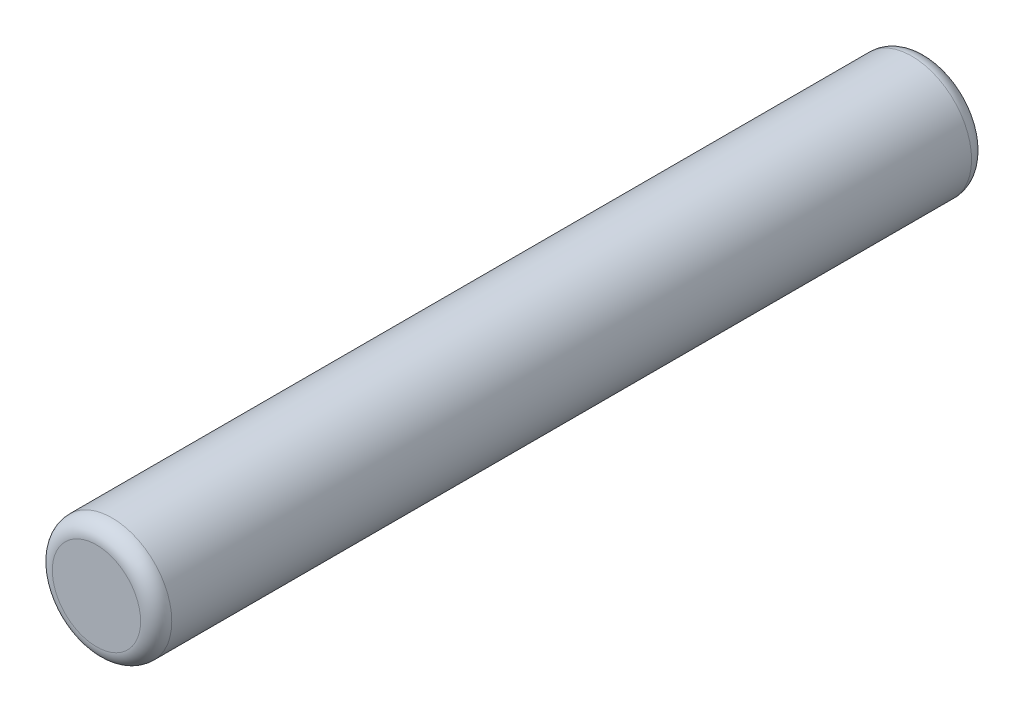
SolidWorks part; units mm, degrees
ref_plane "Plano frontal" through (0, 0, 0) normal (0, 0, 1) x (1, 0, 0)
ref_plane "Plano superior" through (0, 0, 0) normal (0, 1, 0) x (1, 0, 0)
ref_plane "Plano direito" through (0, 0, 0) normal (1, 0, 0) x (0, 0, -1)
sketch "Esboço1" plane through (0, 0, 0) normal (0, 0, 1) x (1, 0, 0)
  circle A0 centre (0, 0) radius 1.15
  dimension "D1" = 2.3
extrude "Ressalto-extrusão1" add sketch "Esboço1" along normal blind 16
fillet "Filete1" radius 0.3 2 edges at (1.15, 0, 0) (1.15, 0, 16)
